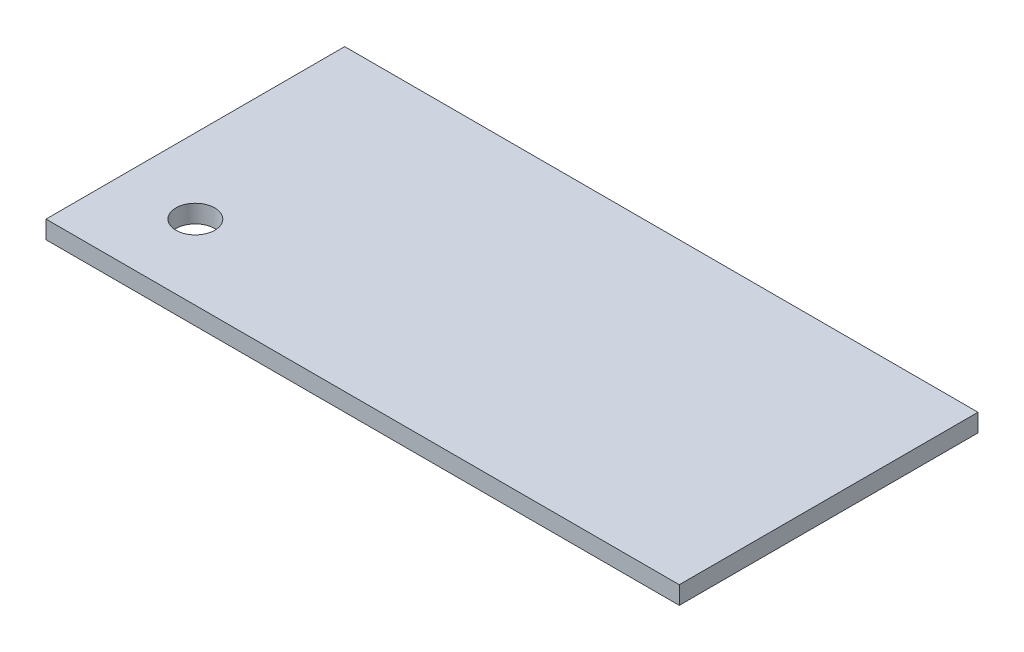
SolidWorks part; units mm, degrees
material "Pine"
ref_plane "Front Plane" through (0, 0, 0) normal (0, 0, 1) x (1, 0, 0)
ref_plane "Top Plane" through (0, 0, 0) normal (0, 1, 0) x (1, 0, 0)
ref_plane "Right Plane" through (0, 0, 0) normal (1, 0, 0) x (0, 0, -1)
sketch "Sketch1" plane through (0, 0, 0) normal (0, 1, 0) x (1, 0, 0)
  line L1 (0, 0) -> (212, 0)
  line L2 (0, 0) -> (0, 100)
  line L3 (0, 100) -> (212, 100)
  line L4 (212, 0) -> (212, 100)
  dimension "D1" = 212
  dimension "D2" = 100
extrude "Boss-Extrude1" add sketch "Sketch1" along normal blind 6
sketch "Sketch2" plane through (0, 6, 0) normal (0, 1, 0) x (1, 0, 0)
  line L0 (0, 100) -> (0, 0) construction
  line L1 (0, 0) -> (212, 0) construction
  circle A0 centre (25, 25) radius 6.5
  dimension "D1" = 13
  dimension "D2" = 25
  dimension "D3" = 25
extrude "Cut-Extrude1" cut sketch "Sketch2" against normal through all
equation "\"BoardThickness\"= 6"
equation "\"D1@Boss-Extrude1\"=\"BoardThickness\""
equation "\"D1@Sketch1\"=200+\"BoardThickness\"*2"
